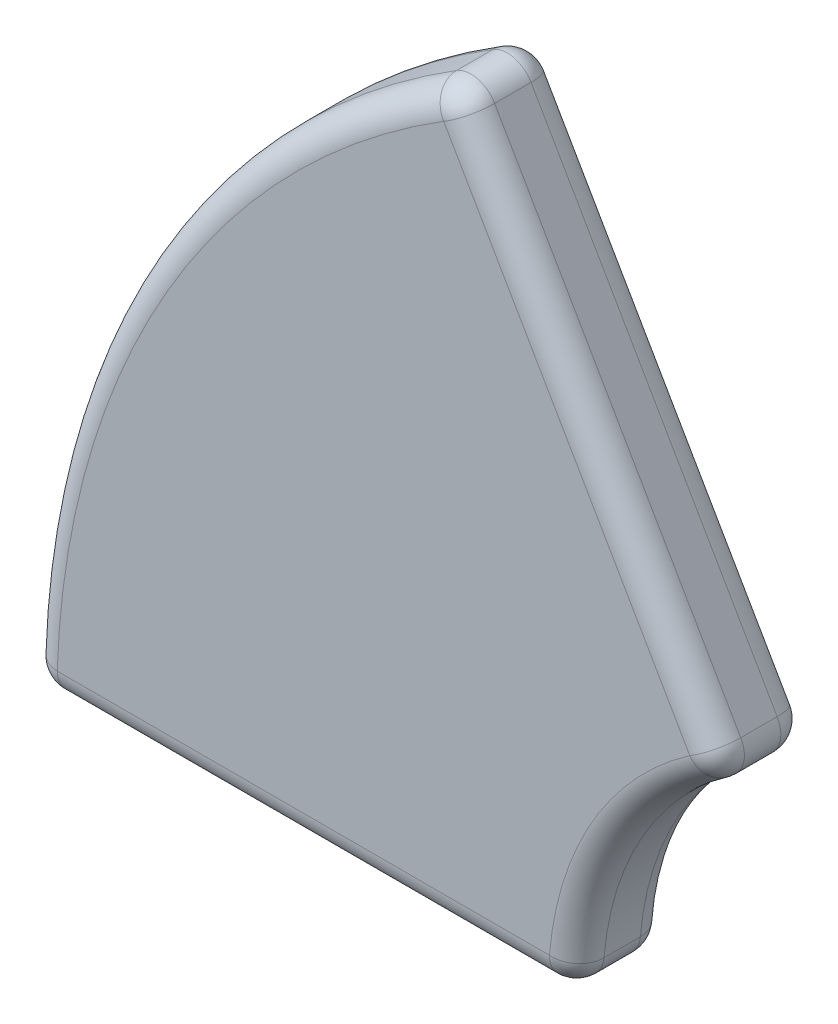
SolidWorks part; units mm, degrees
ref_plane "Front Plane" through (0, 0, 0) normal (0, 0, 1) x (1, 0, 0)
ref_plane "Top Plane" through (0, 0, 0) normal (0, 1, 0) x (1, 0, 0)
ref_plane "Right Plane" through (0, 0, 0) normal (1, 0, 0) x (0, 0, -1)
sketch "Sketch1" plane through (0, 0, 0) normal (0, 0, 1) x (1, 0, 0)
  line L1 (-331.6, 0) -> (-931.6, 0)
  line L3 (-165.8, 287.174) -> (-465.8, 806.7893)
  arc A1 (-465.8, 806.7893) -> (-931.6, 0) centre (0, 0) ccw
  arc A2 (-165.8, 287.174) -> (-331.6, 0) centre (0, 0) ccw
  dimension "D2" = 931.6
  dimension "D3" = 331.6
  dimension "D4" = 60
extrude "Boss-Extrude1" add sketch "Sketch1" along normal blind 100
fillet "Fillet1" radius 30 12 edges at (-331.6, 0, 50) (-931.6, 0, 50) (-465.8, 806.7893, 50) (-315.8, 546.9816, 0) (-315.8, 546.9816, 100) (-165.8, 287.174, 50) (-287.174, 165.8, 0) (-287.174, 165.8, 100) (-631.6, 0, 100) (-631.6, 0, 0) (-806.7893, 465.8, 0) (-806.7893, 465.8, 100)
